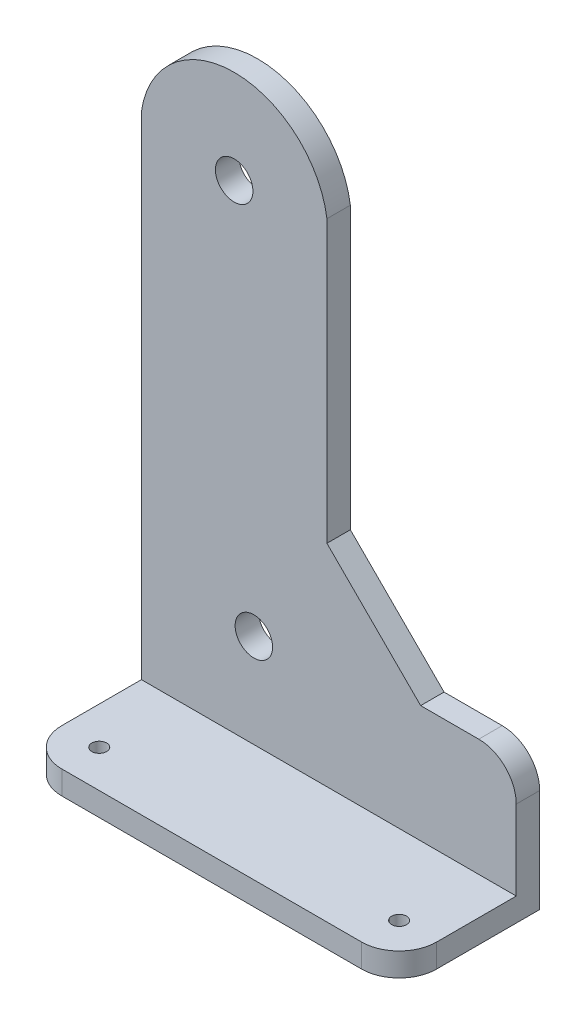
SolidWorks part; units mm, degrees
ref_plane "Front Plane" through (0, 0, 0) normal (0, 0, 1) x (1, 0, 0)
ref_plane "Top Plane" through (0, 0, 0) normal (0, 1, 0) x (1, 0, 0)
ref_plane "Right Plane" through (0, 0, 0) normal (1, 0, 0) x (0, 0, -1)
sketch "Sketch1" plane through (0, 0, 0) normal (0, 0, 1) x (1, 0, 0)
  line L0 (-61.5505, -258.9703) -> (338.4495, -258.9703)
  line L1 (338.4495, -258.9703) -> (338.4495, -148.9703)
  line L6 (298.4495, -108.9703) -> (236.4291, -108.9703)
  line L7 (236.4291, -108.9703) -> (136.4291, -8.9703)
  line L8 (-61.5505, -258.9703) -> (-61.5505, 291.0297)
  line L9 (136.4291, -8.9703) -> (136.4291, 291.0297)
  arc A1 (338.4495, -148.9703) -> (298.4495, -108.9703) centre (298.4495, -148.9703) ccw
  arc A2 (-61.5505, 291.0297) -> (136.4291, 291.0297) centre (37.4393, 276.8516) cw
  point P10 (338.4495, -108.9703)
  dimension "D3" = 300
  dimension "D8" = 40
  dimension "D4" = 100
  dimension "D1" = 400
  dimension "D2" = 550
  dimension "D5" = 150
  dimension "D6" = 45
  dimension "D7" = 100
extrude "Boss-Extrude1" add sketch "Sketch1" along normal blind 25
sketch "Sketch2" plane through (0, 0, 0) normal (0, 0, 1) x (1, 0, 0)
  line L0 (338.4495, -258.9703) -> (338.4495, -148.9703) construction
  line L1 (-61.5505, -258.9703) -> (338.4495, -258.9703)
  line L2 (-61.5505, -258.9703) -> (-61.5505, -233.9703)
  line L3 (-61.5505, -233.9703) -> (338.4495, -233.9703)
  line L4 (338.4495, -258.9703) -> (338.4495, -233.9703)
  dimension "D1" = 25
extrude "Boss-Extrude2" add sketch "Sketch2" along normal blind 150
sketch "Sketch3" plane through (0, -233.9703, 0) normal (0, 1, 0) x (1, 0, 0)
  line L4 (338.4495, -110) -> (338.4495, -150)
  line L5 (338.4495, -150) -> (298.4495, -150)
  line L6 (138.4495, -105.8374) -> (138.4495, -205.9462) construction
  line L7 (-61.5505, -110) -> (-61.5505, -150)
  line L8 (-61.5505, -150) -> (-21.5505, -150)
  arc A0 (338.4495, -110) -> (298.4495, -150) centre (298.4495, -110) cw
  arc A1 (-61.5505, -110) -> (-21.5505, -150) centre (-21.5505, -110) ccw
  point P9 (338.4495, -150)
  dimension "D1" = 40
extrude "Cut-Extrude1" cut sketch "Sketch3" against normal blind 150
sketch "Sketch4" plane through (0, -233.9703, 0) normal (0, 1, 0) x (1, 0, 0)
  line L0 (-21.5505, -110) -> (298.4495, -110) construction
  line L1 (298.4495, -110) -> (290.9999, -107.2528) construction
  circle A0 centre (-21.5505, -110) radius 7.94
  circle A1 centre (298.4495, -110) radius 7.94
  dimension "D1" = 15.88
  dimension "D2" = 15.88
extrude "Cut-Extrude2" cut sketch "Sketch4" against normal blind 150
sketch "Sketch5" plane through (0, 0, 25) normal (0, 0, 1) x (1, 0, 0)
  line L2 (-61.5505, 291.0297) -> (-61.5505, -233.9703) construction
  line L3 (298.4495, -108.9703) -> (236.4291, -108.9703) construction
  circle A0 centre (37.4393, 276.8516) radius 20
  circle A2 centre (58.4495, -133.9703) radius 20
  dimension "D1" = 40
  dimension "D4" = 40
  dimension "D2" = 120
  dimension "D3" = 25
extrude "Cut-Extrude3" cut sketch "Sketch5" against normal blind 150 contours A2 | A0
